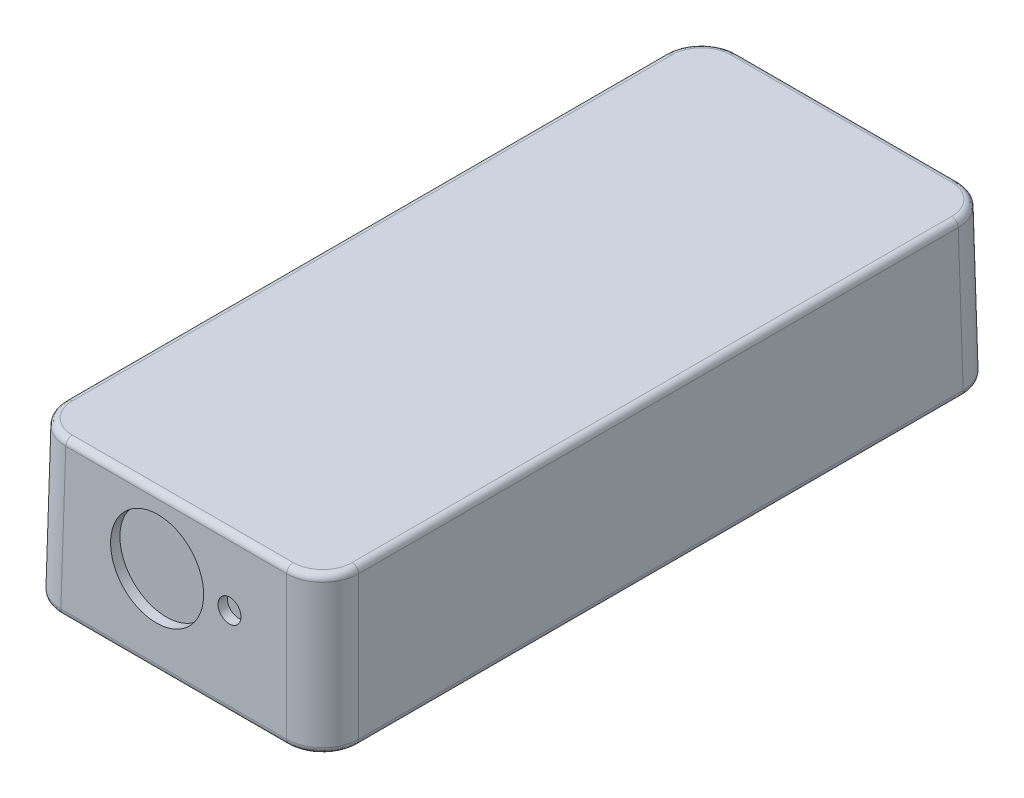
SolidWorks part; units mm, degrees
ref_plane "前视基准面" through (0, 0, 0) normal (0, 0, 1) x (1, 0, 0)
ref_plane "上视基准面" through (0, 0, 0) normal (0, 1, 0) x (1, 0, 0)
ref_plane "右视基准面" through (0, 0, 0) normal (1, 0, 0) x (0, 0, -1)
sketch "草图1" plane through (0, 0, 0) normal (0, 1, 0) x (1, 0, 0)
  line L1 (22.75, -51.65) -> (-22.75, -51.65)
  line L2 (22.75, -51.65) -> (22.75, 51.65)
  line L3 (22.75, 51.65) -> (-22.75, 51.65)
  line L4 (-22.75, -51.65) -> (-22.75, 51.65)
  line L5 (22.75, -51.65) -> (-22.75, 51.65) construction
  line L6 (22.75, 51.65) -> (-22.75, -51.65) construction
  point P0 (0, 0)
  dimension "D1" = 45.5
  dimension "D2" = 103.3
extrude "凸台-拉伸1" add sketch "草图1" along normal blind 23.5 draft 1
fillet "圆角1" radius 5.5 4 edges at (-22.5449, 11.75, -51.4449) (22.5449, 11.75, -51.4449) (-22.5449, 11.75, 51.4449) (22.5449, 11.75, 51.4449)
sketch "草图2" plane through (0, 0, 0) normal (0, 0, 1) x (1, 0, 0)
  line L2 (-16.8406, 23.5) -> (16.8406, 23.5) construction
  line L3 (22.3398, 23.5) -> (22.75, 0) construction
  circle A0 centre (8.2949, 13.45) radius 1.75
  circle A1 centre (-2.7551, 13.45) radius 7.1
  point P10 (22.5449, 11.75)
  dimension "D1" = 14.25
  dimension "D2" = 3.5
  dimension "D3" = 10.05
  dimension "D4" = 14.2
  dimension "D5" = 11.05
extrude "切除-拉伸1" cut sketch "草图2" along normal through all from offset 50
fillet "圆角2" radius 1 16 edges at (22.75, 0, 0) (21.1394, 0, -50.0394) (0, 0, -51.65) (-21.1394, 0, -50.0394) (-22.75, 0, 0) (-21.1394, 0, 50.0394) (0, 0, 51.65) (0, 23.5, 51.2398) (-20.7292, 23.5, 49.6292) (-22.3398, 23.5, 0) (-20.7292, 23.5, -49.6292) (0, 23.5, -51.2398) (20.7292, 23.5, -49.6292) (22.3398, 23.5, 0) (21.1394, 0, 50.0394) (20.7292, 23.5, 49.6292)
